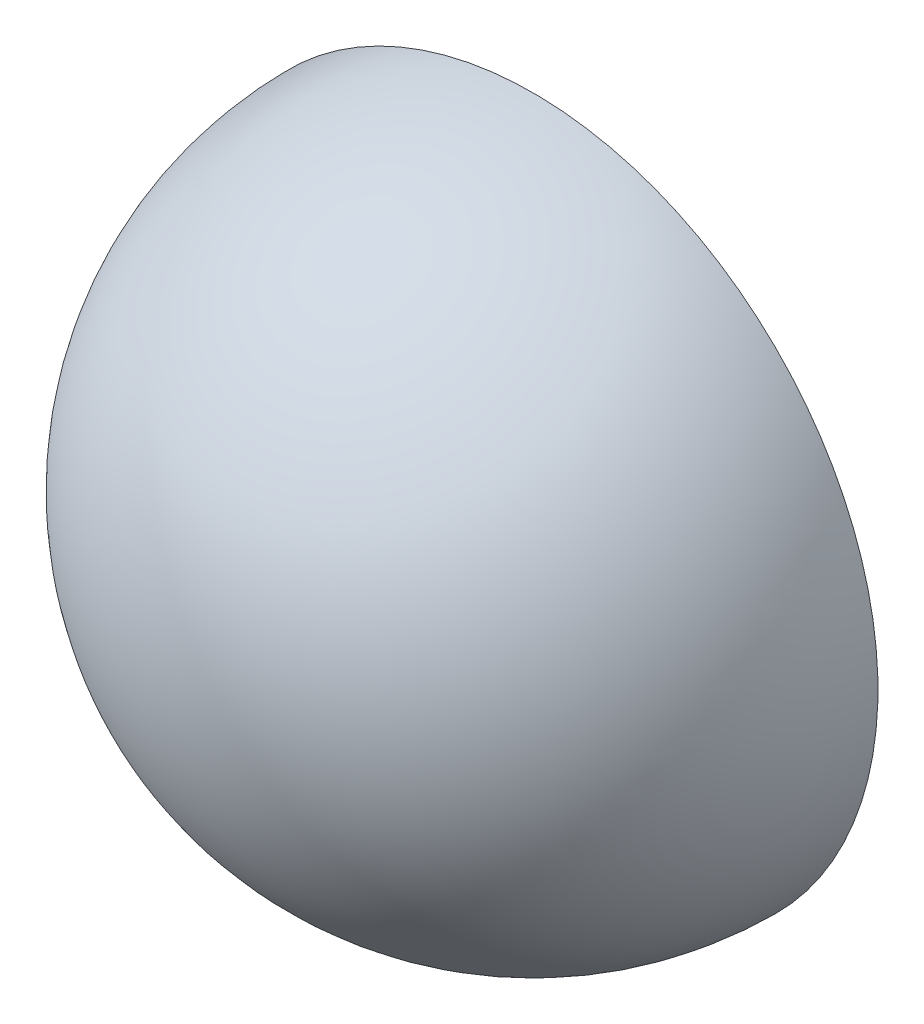
SolidWorks part; units mm, degrees
ref_plane "Front Plane" through (0, 0, 0) normal (0, 0, 1) x (1, 0, 0)
ref_plane "Top Plane" through (0, 0, 0) normal (0, 1, 0) x (1, 0, 0)
ref_plane "Right Plane" through (0, 0, 0) normal (1, 0, 0) x (0, 0, -1)
sketch "Sketch1" plane through (0, 0, 0) normal (0, 0, 1) x (1, 0, 0)
  line L0 (0, 25) -> (0, -25)
  arc A0 (0, -25) -> (0, 25) centre (0, 0) ccw
  dimension "D1" = 50
revolve "Revolve1" add sketch "Sketch1" angle 180 about L0
sketch "Sketch2" plane through (0, 0, 0) normal (0, 0, -1) x (-1, 0, 0)
  line L0 (0, 15) -> (0, -15)
  arc A0 (0, -15) -> (0, 15) centre (0, 0) ccw
  dimension "D1" = 30
revolve "Cut-Revolve1" cut sketch "Sketch2" angle 360 about L0
